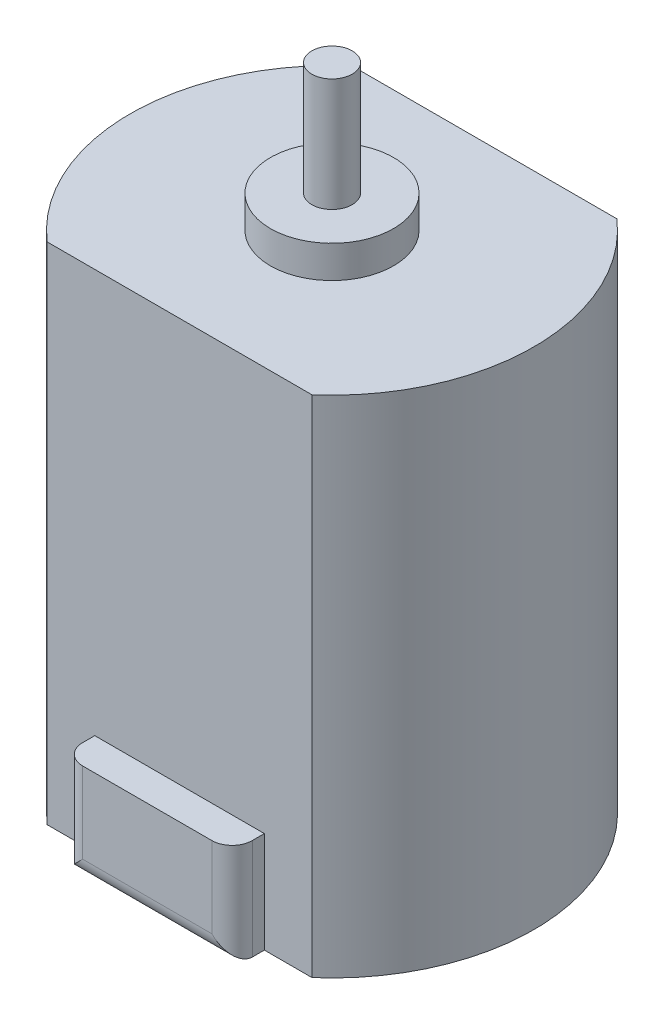
SolidWorks part; units mm, degrees
ref_plane "Front Plane" through (0, 0, 0) normal (0, 0, 1) x (1, 0, 0)
ref_plane "Top Plane" through (0, 0, 0) normal (0, 1, 0) x (1, 0, 0)
ref_plane "Right Plane" through (0, 0, 0) normal (1, 0, 0) x (0, 0, -1)
sketch "Sketch1" plane through (0, 0, 0) normal (0, 1, 0) x (1, 0, 0)
  line L0 (-6.5572, 7.55) -> (6.5572, 7.55)
  line L2 (-55, 0) -> (55, 0) construction
  line L3 (-6.5572, -7.55) -> (6.5572, -7.55)
  circle A0 centre (0, 0) radius 10
  dimension "D1" = 20
  dimension "D2" = 7.55
extrude "Boss-Extrude1" add sketch "Sketch1" along normal blind 25 contours L3 A0 L0
sketch "Sketch2" plane through (0, 25, 0) normal (0, 1, 0) x (1, 0, 0)
  circle A0 centre (0, 0) radius 3.05
  dimension "D1" = 6.1
extrude "Boss-Extrude2" add sketch "Sketch2" along normal blind 1.6
sketch "Sketch3" plane through (0, 26.6, 0) normal (0, 1, 0) x (1, 0, 0)
  circle A0 centre (0, 0) radius 1
  dimension "D1" = 2
extrude "Boss-Extrude3" add sketch "Sketch3" along normal blind 5.6
sketch "Sketch4" plane through (0, 0, 0) normal (0, -1, 0) x (1, 0, 0)
  circle A0 centre (0, 0) radius 4.95
  dimension "D1" = 9.9
extrude "Boss-Extrude4" add sketch "Sketch4" along normal blind 2.3
sketch "Sketch5" plane through (0, -2.3, 0) normal (0, -1, 0) x (1, 0, 0)
  circle A0 centre (0, 0) radius 1
  point P3 (0, 0)
  dimension "D1" = 2
extrude "Boss-Extrude5" add sketch "Sketch5" along normal blind 1.5
sketch "Sketch6" plane through (0, 0, 7.55) normal (0, 0, 1) x (1, 0, 0)
  line L0 (-6.5572, 0) -> (6.5572, 0) construction
  line L1 (-4.2, 5) -> (4.2, 5)
  line L2 (-4.2, 5) -> (-4.2, 0)
  line L3 (-4.2, 0) -> (4.2, 0)
  line L4 (4.2, 5) -> (4.2, 0)
  line L5 (0, 0) -> (0, 5) construction
  line L6 (-4.2, 2.5) -> (4.2, 2.5) construction
  point P128 (0, 2.5)
  dimension "D1" = 8.4
  dimension "D2" = 5
extrude "Boss-Extrude6" add sketch "Sketch6" along normal blind 1.6
fillet "Fillet1" radius 1 3 edges at (-4.2, 2.5, 9.15) (4.2, 2.5, 9.15) (0, 0, 9.15)
